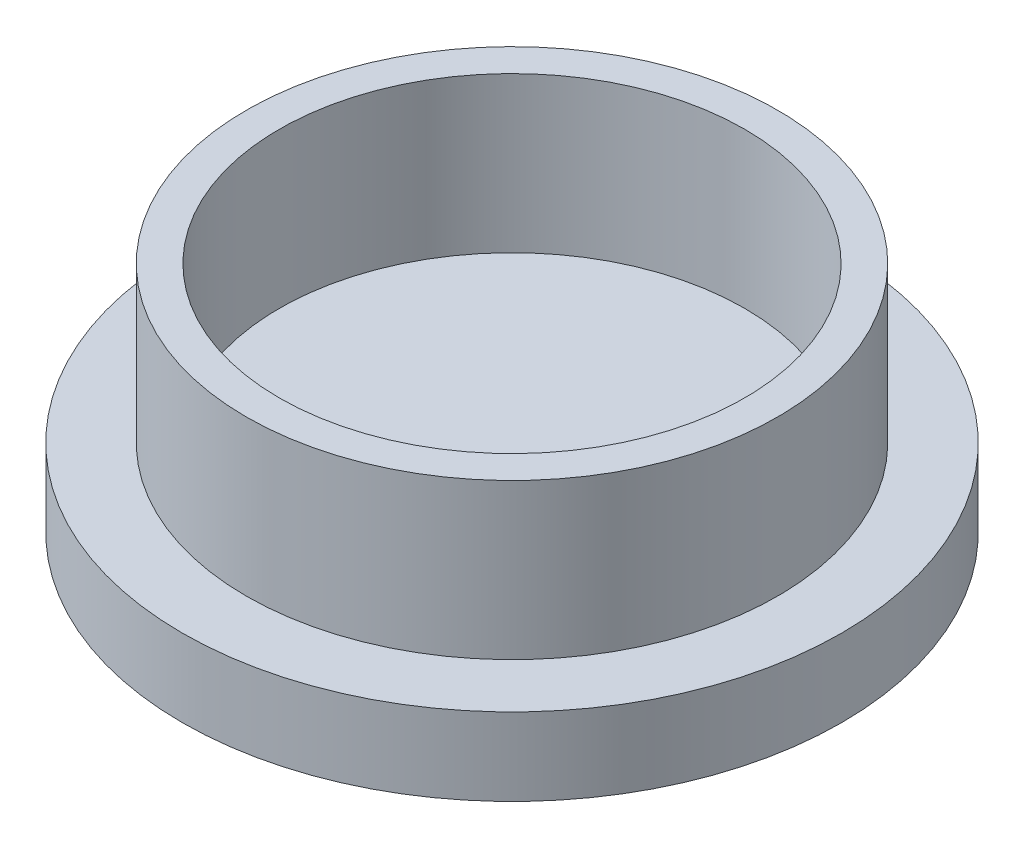
SolidWorks part; units mm, degrees
ref_plane "Front Plane" through (0, 0, 0) normal (0, 0, 1) x (1, 0, 0)
ref_plane "Top Plane" through (0, 0, 0) normal (0, 1, 0) x (1, 0, 0)
ref_plane "Right Plane" through (0, 0, 0) normal (1, 0, 0) x (0, 0, -1)
sketch "Sketch1" plane through (0, 0, 0) normal (0, 1, 0) x (1, 0, 0)
  circle A0 centre (0, 0) radius 3.425
  dimension "D1" = 6.85
extrude "Boss-Extrude1" add sketch "Sketch1" along normal blind 2
sketch "Sketch2" plane through (0, 0, 0) normal (0, -1, 0) x (1, 0, 0)
  circle A0 centre (0, 0) radius 4.25
  dimension "D1" = 8.5
extrude "Boss-Extrude2" add sketch "Sketch2" along normal blind 1
sketch "Sketch3" plane through (0, 2, 0) normal (0, 1, 0) x (1, 0, 0)
  circle A0 centre (0, 0) radius 3
  dimension "D1" = 6
extrude "Cut-Extrude1" cut sketch "Sketch3" against normal blind 2
